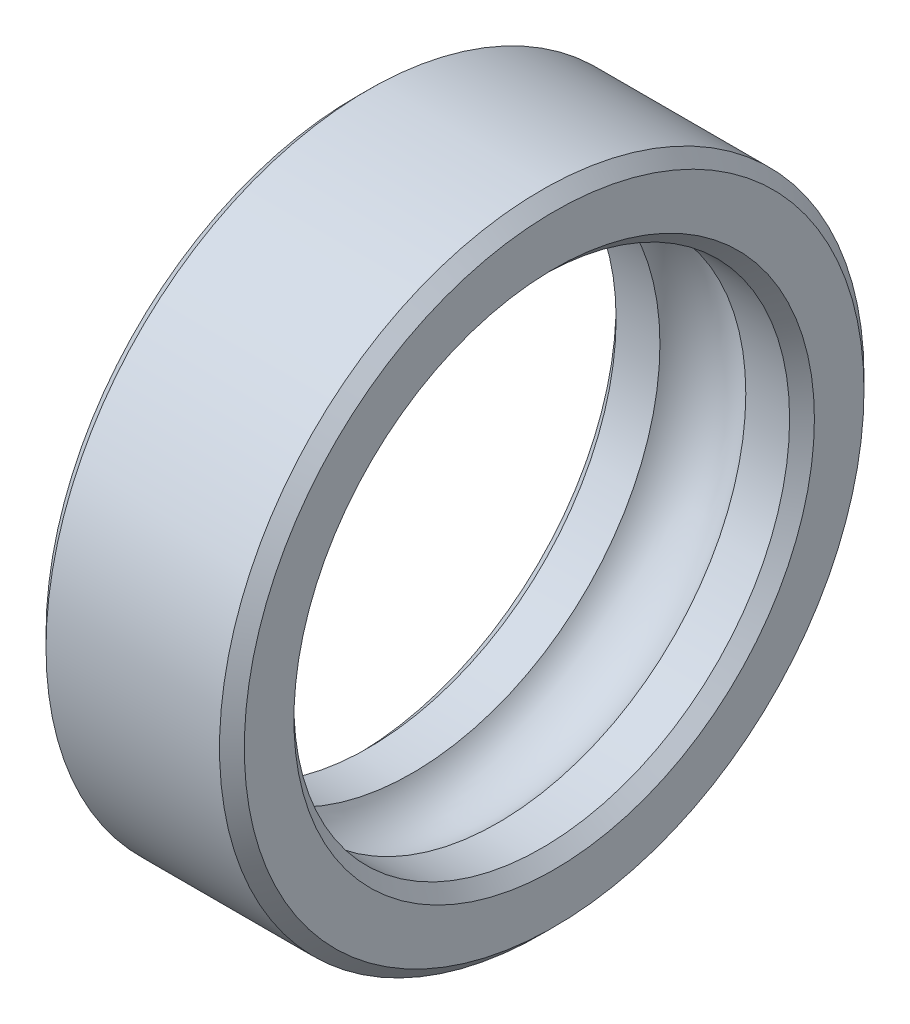
SolidWorks part; units mm, degrees
ref_plane "Ön Düzlem" through (0, 0, 0) normal (0, 0, 1) x (1, 0, 0)
ref_plane "Üst Düzlem" through (0, 0, 0) normal (0, 1, 0) x (1, 0, 0)
ref_plane "Sağ Düzlem" through (0, 0, 0) normal (1, 0, 0) x (0, 0, -1)
sketch "Çizim1" plane through (0, 0, 0) normal (0, 0, 1) x (1, 0, 0)
  line L0 (0, 0) -> (-11.7663, 0) construction
  line L1 (0, 10) -> (0, 13)
  line L2 (0, 13) -> (-8, 13)
  line L3 (-8, 13) -> (-8, 10)
  line L4 (-8, 10) -> (-5.7321, 10)
  line L5 (-2.2679, 10) -> (0, 10)
  arc A2 (-5.7321, 10) -> (-2.2679, 10) centre (-4, 9) cw
  point P2 (-1.9513, 10)
  point P11 (0, 0)
  dimension "D1" = 8
  dimension "D2" = 2
  dimension "D3" = 3
  dimension "D4" = 3
  dimension "D5" = 1
  dimension "D7" = 26
revolve "Döndür1" add sketch "Çizim1" angle 360 about L0
chamfer "Pah1" distance 0.5 angle 45 4 edges at (-8, 0, -13) (0, 0, -13) (-8, 0, -10) (0, 0, -10)
